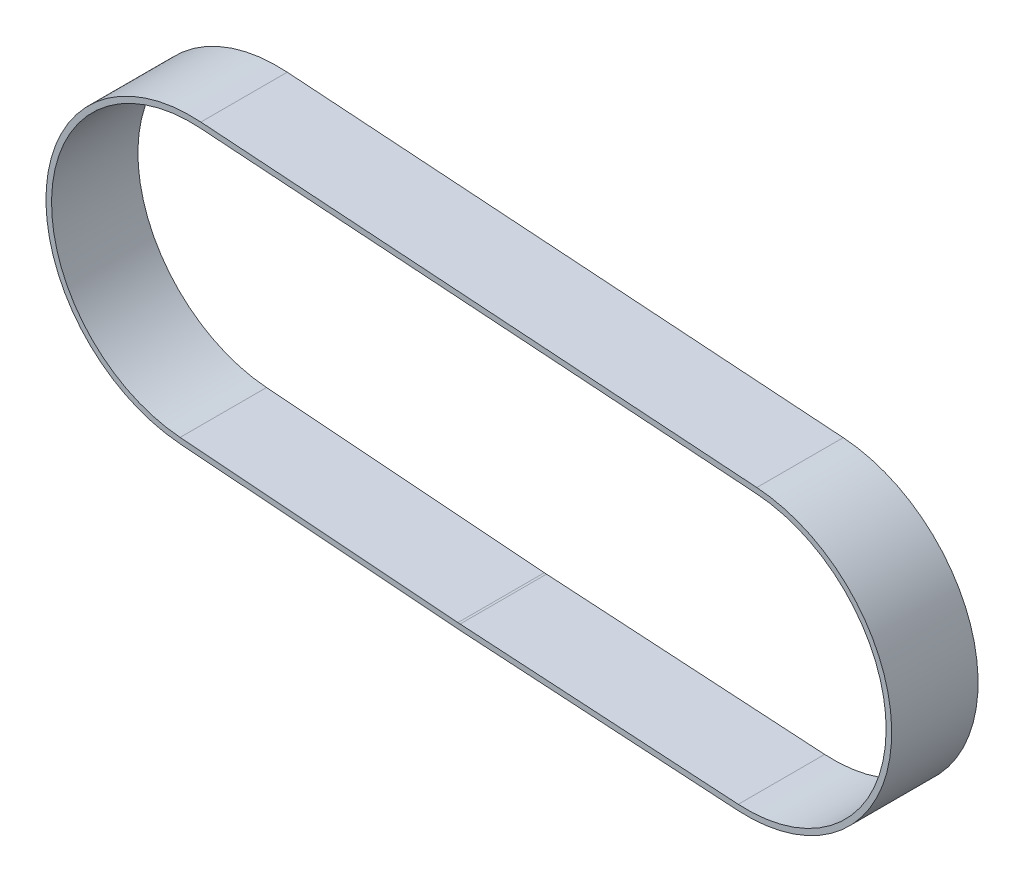
SolidWorks part; units mm, degrees
ref_plane "Front Plane" through (0, 0, 0) normal (0, 0, 1) x (1, 0, 0)
ref_plane "Top Plane" through (0, 0, 0) normal (0, 1, 0) x (1, 0, 0)
ref_plane "Right Plane" through (0, 0, 0) normal (1, 0, 0) x (0, 0, -1)
sketch "Sketch2" plane through (0, 0, 0) normal (0, 0, 1) x (1, 0, 0)
  line L0 (0, 0) -> (1, 0) construction
  line L1 (0, 0) -> (0, 1) construction
  line L2 (-3.8092, -49.304) -> (95.8939, -57.004)
  line L3 (96.6825, -57.0587) -> (196.4948, -63.1815)
  line L4 (203.0121, 36.6051) -> (3.4966, 50.428)
  arc A0 (3.4966, 50.428) -> (-3.8092, -49.304) centre (0.0408, 0.5475) ccw
  arc A1 (95.8939, -57.004) -> (96.6825, -57.0587) centre (99.7439, -7.1525) ccw
  arc A2 (196.4948, -63.1815) -> (203.0121, 36.6051) centre (199.5563, -13.2753) ccw
extrude "Extrude-Thin2" add sketch "Sketch2" against normal blind 30 and the other way blind 1 thin
